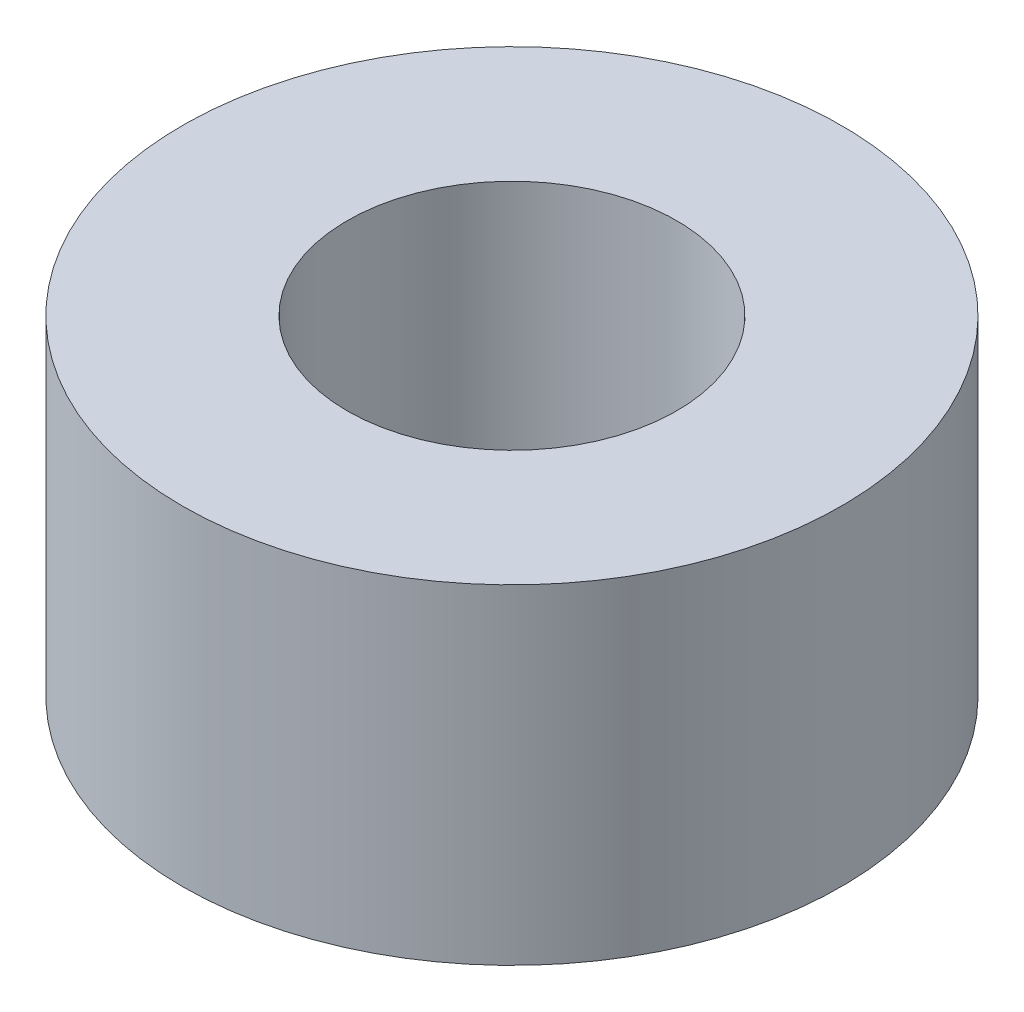
SolidWorks part; units mm, degrees
ref_plane "Front Plane" through (0, 0, 0) normal (0, 0, 1) x (1, 0, 0)
ref_plane "Top Plane" through (0, 0, 0) normal (0, 1, 0) x (1, 0, 0)
ref_plane "Right Plane" through (0, 0, 0) normal (1, 0, 0) x (0, 0, -1)
sketch "Sketch1" plane through (0, 0, 0) normal (0, 1, 0) x (1, 0, 0)
  circle A0 centre (0, 0) radius 1.5
  circle A1 centre (0, 0) radius 3
  dimension "D1" = 3
  dimension "D2" = 6
extrude "Boss-Extrude1" add sketch "Sketch1" along normal blind 3
